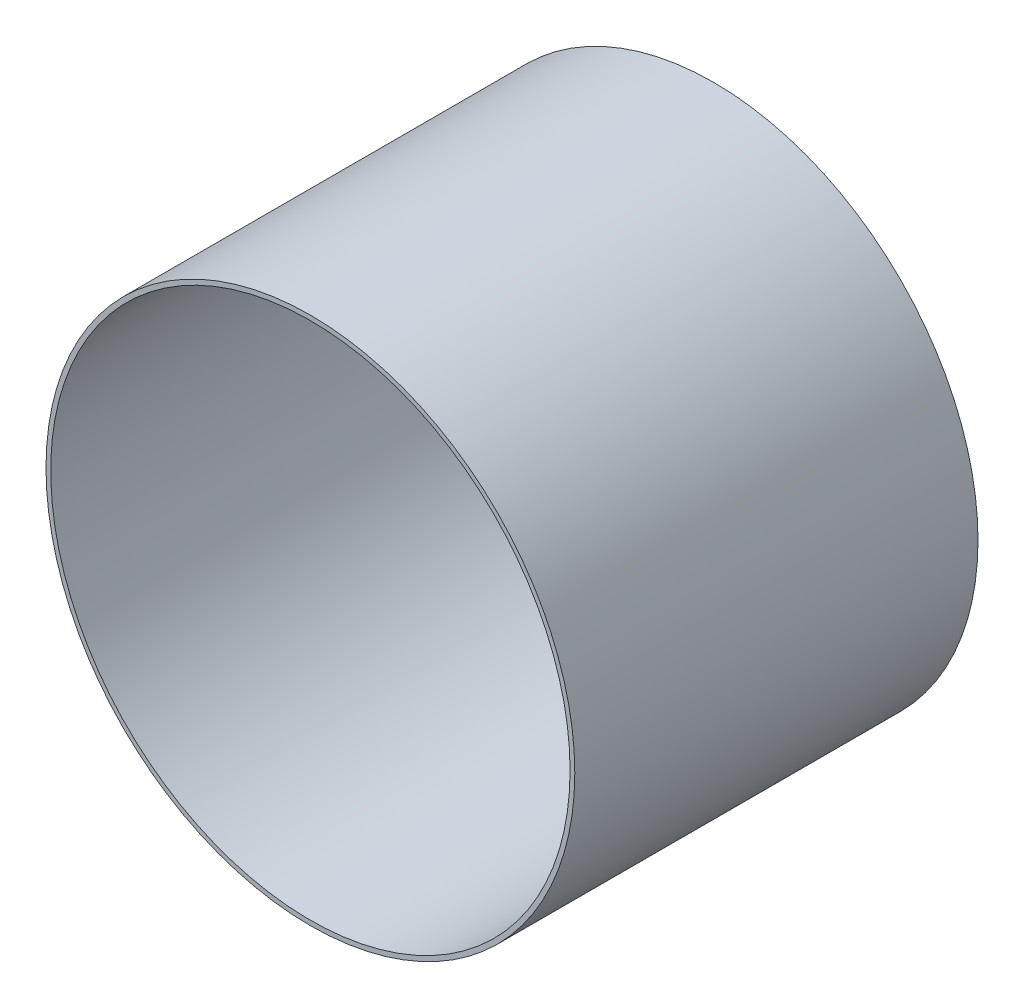
SolidWorks part; units mm, degrees
ref_plane "Front Plane" through (0, 0, 0) normal (0, 0, 1) x (1, 0, 0)
ref_plane "Top Plane" through (0, 0, 0) normal (0, 1, 0) x (1, 0, 0)
ref_plane "Right Plane" through (0, 0, 0) normal (1, 0, 0) x (0, 0, -1)
sketch "Sketch1" plane through (0, 0, 0) normal (0, 0, 1) x (1, 0, 0)
  circle A0 centre (0, 0) radius 69.85
  circle A1 centre (0, 0) radius 71.12
  dimension "D1" = 142.24
  dimension "D2" = 139.7
extrude "Extrude1" add sketch "Sketch1" along normal blind 108.458
